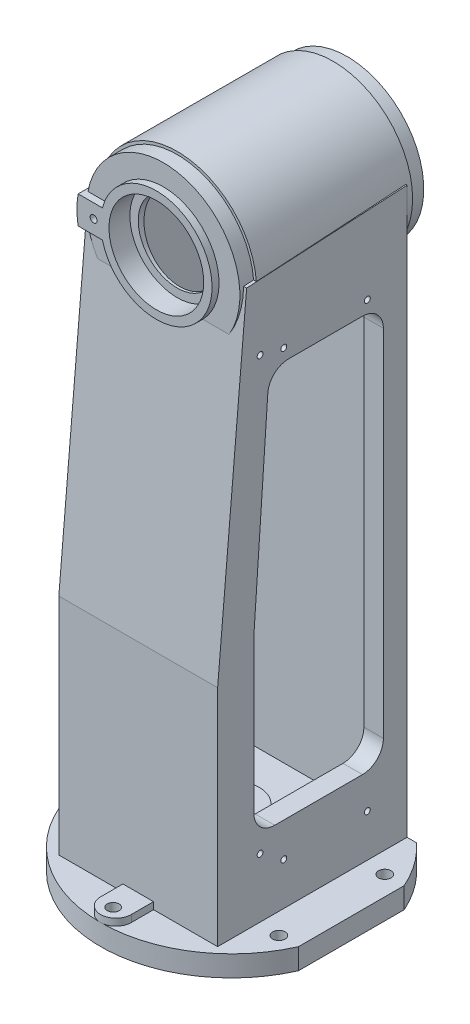
SolidWorks part; units mm, degrees
ref_plane "前视基准面" through (0, 0, 0) normal (0, 0, 1) x (1, 0, 0)
ref_plane "上视基准面" through (0, 0, 0) normal (0, 1, 0) x (1, 0, 0)
ref_plane "右视基准面" through (0, 0, 0) normal (1, 0, 0) x (0, 0, -1)
sketch "草图1" plane through (0, 0, 0) normal (0, 1, 0) x (1, 0, 0)
  line L0 (-86, 37.9473) -> (-86, -37.9473)
  line L1 (0, 0) -> (0, -70) construction
  line L2 (86, 37.9473) -> (86, -37.9473)
  line L5 (0, 0) -> (-62.7375, 0) construction
  line L6 (-63.8357, 69) -> (63.8357, 69)
  arc A0 (63.8357, 69) -> (86, 37.9473) centre (0, 0) cw
  arc A4 (-86, 37.9473) -> (-63.8357, 69) centre (0, 0) cw
  arc A5 (86, -37.9473) -> (-86, -37.9473) centre (0, 0) cw
  dimension "D2" = 69
  dimension "D3" = 94
  dimension "D1" = 172
extrude "凸台-拉伸1" add sketch "草图1" along normal blind 15
sketch "草图2" plane through (0, 15, 0) normal (0, 1, 0) x (1, 0, 0)
  line L0 (0, 0) -> (0, 57.4262) construction
  line L1 (0, 0) -> (-113.6406, 0) construction
  circle A0 centre (-72, 38) radius 4.5
  circle A1 centre (-72, -38) radius 4.5
  circle A2 centre (72, -38) radius 4.5
  circle A3 centre (72, 38) radius 4.5
  dimension "D3" = 9
  dimension "D1" = 144
  dimension "D2" = 76
extrude "切除-拉伸1" cut sketch "草图2" against normal through all
sketch "草图3" plane through (0, 15, 0) normal (0, 1, 0) x (1, 0, 0)
  line L0 (-11, -65) -> (-11, -83)
  line L1 (11, -83) -> (11, -65)
  line L2 (11, -65) -> (-11, -65)
  line L3 (0, 0) -> (0, -70.1629) construction
  arc A0 (-11, -83) -> (11, -83) centre (0, -83) ccw
  dimension "D1" = 83
  dimension "D2" = 11
  dimension "D3" = 18
extrude "凸台-拉伸2" add sketch "草图3" along normal blind 5
hole_wizard "孔1" positions "草图5" profile "草图4" legacy
sketch "草图5" plane through (0, 0, 0) normal (0, -1, 0) x (1, 0, 0)
  point P1 (0, 85)
  dimension "D1" = 85
sketch "草图4" plane through (0, 0, 85) normal (1, 0, 0) x (0, 0, -1)
  line L0 (0, 0) -> (0, 60)
  line L1 (0, 60) -> (4.25, 60)
  line L2 (4.25, 60) -> (4.25, 10)
  line L3 (4.25, 10) -> (7, 10)
  line L4 (7, 10) -> (7, 0)
  line L5 (7, 0) -> (0, 0)
  line L6 (0, 110) -> (0, -10) construction
  dimension "直径" = 8.5
  dimension "深度" = 60
  dimension "柱坑直径" = 14
  dimension "柱坑深度" = 10
sketch "草图7" plane through (0, 0, 0) normal (1, 0, 0) x (0, 0, -1)
  line L0 (-67, 15) -> (-67, 176)
  line L1 (-37.9473, 15) -> (-94, 15) construction
  line L2 (-94, 20) -> (-94, 15) construction
  line L3 (-67, 15) -> (69, 15)
  line L4 (-37.9473, 15) -> (37.9473, 15) construction
  line L5 (69, 15) -> (69, 420.4446)
  line L6 (69, 15) -> (69, 0) construction
  line L10 (-67, 176) -> (-46.172, 414.0647)
  line L12 (-46.172, 414.0647) -> (69, 420.4446)
  line L14 (-83, 20) -> (-65, 20) construction
  dimension "D1" = 27
  dimension "D2" = 156
  dimension "D3" = 175
extrude "凸台-拉伸3" add sketch "草图7" along normal mid plane 114
ref_plane "基准面1" through (0, 0, 54) normal (0, 0, 1) x (1, 0, 0)
sketch "草图8" plane through (0, 0, 54) normal (0, 0, 1) x (1, 0, 0)
  line L0 (-86, 0) -> (86, 0) construction
  circle A0 centre (0, 410) radius 40
  dimension "D1" = 80
  dimension "D2" = 410
extrude "凸台-拉伸4" add sketch "草图8" against normal blind 5 separate body
sketch "草图9" plane through (0, 0, 49) normal (0, 0, -1) x (-1, 0, 0)
  circle A0 centre (0, 410) radius 55
  dimension "D1" = 110
extrude "凸台-拉伸5" add sketch "草图9" along normal blind 10
sketch "草图10" plane through (0, 0, 39) normal (0, 0, -1) x (-1, 0, 0)
  circle A0 centre (0, 410) radius 57
  dimension "D1" = 114
extrude "凸台-拉伸6" add sketch "草图10" along normal blind 112
sketch "草图11" plane through (0, 0, -73) normal (0, 0, -1) x (-1, 0, 0)
  circle A0 centre (0, 410) radius 55
  dimension "D1" = 110
extrude "凸台-拉伸7" add sketch "草图11" along normal blind 10
sketch "草图12" plane through (0, 0, -83) normal (0, 0, -1) x (-1, 0, 0)
  circle A0 centre (0, 410) radius 40
  dimension "D1" = 80
extrude "凸台-拉伸8" add sketch "草图12" along normal blind 10
sketch "草图13" plane through (0, 0, 54) normal (0, 0, 1) x (1, 0, 0)
  circle A0 centre (0, 410) radius 34
  dimension "D1" = 68
extrude "切除-拉伸2" cut sketch "草图13" against normal blind 15
sketch "草图14" plane through (0, 0, -93) normal (0, 0, -1) x (-1, 0, 0)
  circle A0 centre (0, 410) radius 34
  dimension "D1" = 68
extrude "切除-拉伸3" cut sketch "草图14" against normal blind 15
sketch "草图15" plane through (0, 0, -78) normal (0, 0, -1) x (-1, 0, 0)
  circle A0 centre (0, 410) radius 28
  dimension "D1" = 56
extrude "切除-拉伸4" cut sketch "草图15" against normal through all
ref_plane "基准面2" through (0, 0, 34) normal (0, 0, 1) x (1, 0, 0)
sketch "草图16" plane through (0, 0, 34) normal (0, 0, 1) x (1, 0, 0)
  circle A0 centre (0, 410) radius 43
  dimension "D1" = 86
extrude "切除-拉伸5" cut sketch "草图16" against normal blind 105
sketch "草图17" plane through (0, 0, 0) normal (1, 0, 0) x (0, 0, -1)
  line L0 (-55, 29) -> (-55, 179)
  line L1 (-55, 179) -> (-34, 419.0311)
  line L2 (-34, 367) -> (-34, 453) construction
  line L3 (-34, 419.0311) -> (57, 419.0311)
  line L4 (57, 419.0311) -> (57, 29)
  line L5 (57, 29) -> (-55, 29)
  line L6 (-67, 176) -> (-67, 15) construction
  line L7 (69, 15) -> (69, 410) construction
  line L8 (37.9473, 0) -> (69, 0) construction
  line L9 (-46.172, 414.0647) -> (-67, 176) construction
  dimension "D1" = 12
  dimension "D2" = 12
  dimension "D3" = 29
  dimension "D4" = 150
extrude "切除-拉伸6" cut sketch "草图17" against normal mid plane 86
sketch "草图18" plane through (57, 0, 0) normal (1, 0, 0) x (0, 0, -1)
  line L0 (-41, 70) -> (52, 70)
  line L1 (52, 70) -> (52, 355)
  line L2 (52, 355) -> (-30, 355)
  line L3 (-30, 355) -> (-41, 195)
  line L4 (-41, 195) -> (-41, 70)
  line L5 (37.9473, 0) -> (69, 0) construction
  line L6 (69, 15) -> (69, 410) construction
  dimension "D1" = 70
  dimension "D2" = 285
  dimension "D3" = 93
  dimension "D4" = 82
  dimension "D5" = 17
  dimension "D6" = 125
extrude "切除-拉伸7" cut sketch "草图18" against normal up to next
fillet "圆角1" radius 15 4 edges at (50, 70, 41) (50, 70, -52) (50, 355, 30) (50, 355, -52)
sketch "草图19" plane through (0, 29, 0) normal (0, 1, 0) x (1, 0, 0)
  circle A0 centre (0, 0) radius 20
  dimension "D1" = 40
extrude "凸台-拉伸10" add sketch "草图19" along normal blind 13
hole_wizard "M20x2.5 螺纹孔1" positions "草图21" profile "草图20" tap size "M20x2.5" standard "JIS"
sketch "草图21" plane through (0, 0, 0) normal (0, -1, 0) x (1, 0, 0)
  point P1 (0, 0)
sketch "草图20" plane through (0, 0, 0) normal (1, 0, 0) x (0, 0, -1)
  line L0 (0, 0) -> (0, 47.2575)
  line L1 (0, 47.2575) -> (8.75, 42)
  line L2 (8.75, 42) -> (8.75, 0)
  line L5 (8.75, 0) -> (0, 0)
  line L10 (0, 47.2575) -> (-8.75, 42) construction
  line L11 (0, -6.35) -> (0, 107.95) construction
  dimension "螺纹孔钻头直径" = 17.5
  dimension "螺纹孔钻头深度" = 42
  dimension "导头角度" = 118
cosmetic thread "孔螺蚊线1" parameters "D1"=40, "D2"=20
sketch "草图22" plane through (0, 0, 54) normal (0, 0, 1) x (1, 0, 0)
  line L0 (-56.116, 420) -> (-38.7298, 420)
  line L1 (0, 410) -> (-95.1301, 410) construction
  line L2 (-56.116, 400) -> (-38.7298, 400)
  arc A0 (56.8251, 414.462) -> (-56.8251, 414.462) centre (0, 410) ccw construction
  circle A1 centre (0, 410) radius 40 construction
  arc A2 (-38.7298, 420) -> (-38.7298, 400) centre (0, 410) ccw
  arc A3 (-56.116, 420) -> (-56.116, 400) centre (0, 410) ccw
  dimension "D1" = 20
extrude "凸台-拉伸11" add sketch "草图22" against normal up to surface (15 mm away) up to face at (0, 440.231, 39)
hole_wizard "M6x1.0 螺纹孔1" positions "草图24" profile "草图23" tap size "M6x1.0" standard "JIS"
sketch "草图24" plane through (0, 0, 54) normal (0, 0, 1) x (1, 0, 0)
  line L0 (0, 410) -> (-45, 410) construction
  point P1 (-45, 410)
  dimension "D1" = 45
sketch "草图23" plane through (-45, 410, 54) normal (1, 0, 0) x (0, -1, 0)
  line L0 (0, 0) -> (0, 16.5022)
  line L1 (0, 16.5022) -> (2.5, 15)
  line L2 (2.5, 15) -> (2.5, 0)
  line L5 (2.5, 0) -> (0, 0)
  line L10 (0, 16.5022) -> (-2.5, 15) construction
  line L11 (0, -6.35) -> (0, 107.95) construction
  dimension "螺纹孔钻头直径" = 5
  dimension "螺纹孔钻头深度" = 15
  dimension "导头角度" = 118
cosmetic thread "孔螺蚊线2" parameters "D1"=12, "D2"=6
sketch "草图25" plane through (-43, 0, 0) normal (1, 0, 0) x (0, 0, -1)
  line L0 (-31, 138) -> (-31, 93) construction
  line L1 (-8.5, 138) -> (-8.5, 93)
  line L2 (-53.5, 138) -> (-53.5, 93)
  arc A0 (-8.5, 138) -> (-53.5, 138) centre (-31, 138) ccw
  arc A1 (-53.5, 93) -> (-8.5, 93) centre (-31, 93) ccw
  point P2 (-31, 115.5)
  dimension "D3" = 22.5
  dimension "D1" = 93
  dimension "D2" = 45
  dimension "D4" = 31
extrude "切除-拉伸8" cut sketch "草图25" against normal blind 3
sketch "草图26" plane through (-46, 0, 0) normal (1, 0, 0) x (0, 0, -1)
  circle A0 centre (-31, 138) radius 15
  circle A1 centre (-31, 93) radius 15
  dimension "D1" = 30
extrude "切除-拉伸9" cut sketch "草图26" against normal through all
sketch "草图27" plane through (-57, 0, 0) normal (-1, 0, 0) x (0, 0, 1)
  line L0 (6, 138) -> (6, 68)
  line L1 (6, 68) -> (56, 68)
  line L2 (56, 68) -> (56, 138)
  arc A0 (56, 138) -> (6, 138) centre (31, 138) ccw
  circle A1 centre (31, 138) radius 15 construction
  circle A2 centre (31, 93) radius 15 construction
  dimension "D1" = 25
  dimension "D2" = 25
extrude "切除-拉伸10" cut sketch "草图27" against normal blind 2
sketch "草图28" plane through (0, 0, -69) normal (0, 0, -1) x (-1, 0, 0)
  line L0 (-63.8357, 0) -> (63.8357, 0) construction
  circle A0 centre (0, 20) radius 12
  dimension "D2" = 24
  dimension "D1" = 20
extrude "凸台-拉伸12" add sketch "草图28" along normal blind 14
hole_wizard "M12x1.75 螺纹孔2" positions "草图30" profile "草图31" tap size "M12x1.75" standard "JIS"
sketch "草图30" plane through (0, 0, -83) normal (0, 0, -1) x (-1, 0, 0)
  point P1 (0, 20)
sketch "草图31" plane through (0, 20, -83) normal (1, 0, 0) x (0, 1, 0)
  line L0 (0, 0) -> (0, 74.25)
  line L1 (0, 74.25) -> (5.1, 74.25)
  line L2 (5.1, 74.25) -> (5.1, 0)
  line L5 (5.1, 0) -> (0, 0)
  line L11 (0, -6.35) -> (0, 107.95) construction
  dimension "通孔螺纹孔钻头直径" = 10.2
  dimension "通孔螺纹孔钻头深度" = 74.25
cosmetic thread "孔螺蚊线3" parameters "D2"=12
hole_wizard "M5x0.8 螺纹孔1" positions "草图33" profile "草图32" tap size "M5x0.8" standard "JIS"
sketch "草图33" plane through (57, 0, 0) normal (1, 0, 0) x (0, 0, -1)
  line L0 (52, 212.5) -> (-136.621, 212.5) construction
  line L1 (52, 85) -> (52, 340) construction
  line L3 (-41, 195) -> (-41, 85) construction
  point P1 (-36.5, 367.5)
  point P3 (-36.5, 57.5)
  dimension "D1" = 310
  dimension "D2" = 4.5
cosmetic thread "孔螺蚊线4" parameters "D2"=5
cosmetic thread "孔螺蚊线5" parameters "D2"=5
sketch "草图32" plane through (57, 367.5, 36.5) normal (0, 1, 0) x (0, 0, -1)
  line L0 (0, 0) -> (0, 14)
  line L1 (0, 14) -> (2.1, 14)
  line L2 (2.1, 14) -> (2.1, 0)
  line L5 (2.1, 0) -> (0, 0)
  line L11 (0, -6.35) -> (0, 107.95) construction
  dimension "通孔螺纹孔钻头直径" = 4.2
  dimension "通孔螺纹孔钻头深度" = 14
hole_wizard "M5x0.8 螺纹孔2" positions "草图35" profile "草图34" tap size "M5x0.8" standard "JIS"
sketch "草图35" plane through (57, 0, 0) normal (1, 0, 0) x (0, 0, -1)
  line L0 (52, 85) -> (52, 340) construction
  line L1 (37, 355) -> (-15.9958, 355) construction
  point P0 (40.5, 363.5)
  point P1 (-19.5, 363.5)
  point P7 (-19.5, 45.5)
  point P9 (40.5, 45.5)
  dimension "D1" = 60
  dimension "D2" = 11.5
  dimension "D3" = 8.5
  dimension "D4" = 318
cosmetic thread "孔螺蚊线6" parameters "D2"=5
cosmetic thread "孔螺蚊线7" parameters "D2"=5
cosmetic thread "孔螺蚊线8" parameters "D2"=5
cosmetic thread "孔螺蚊线9" parameters "D2"=5
sketch "草图34" plane through (57, 363.5, -40.5) normal (0, 1, 0) x (0, 0, -1)
  line L0 (0, 0) -> (0, 14)
  line L1 (0, 14) -> (2.1, 14)
  line L2 (2.1, 14) -> (2.1, 0)
  line L5 (2.1, 0) -> (0, 0)
  line L11 (0, -6.35) -> (0, 107.95) construction
  dimension "通孔螺纹孔钻头直径" = 4.2
  dimension "通孔螺纹孔钻头深度" = 14
hole_wizard "M5x0.8 螺纹孔3" positions "草图37" profile "草图36" tap size "M5x0.8" standard "JIS"
sketch "草图37" plane through (-57, 0, 0) normal (-1, 0, 0) x (0, 0, 1)
  line L0 (-69, 15) -> (-69, 410) construction
  line L1 (-69, 0) -> (-37.9473, 0) construction
  line L2 (-69, 15) -> (-69, 410) construction
  point P1 (-24, 145)
  point P3 (-31.5, 315)
  point P5 (18.5, 315)
  point P11 (-57, 110)
  point P13 (-42, 110)
  dimension "D2" = 50
  dimension "D3" = 37.5
  dimension "D4" = 145
  dimension "D5" = 45
  dimension "D6" = 315
  dimension "D7" = 12
  dimension "D8" = 15
  dimension "D9" = 110
sketch "草图36" plane through (-57, 145, -24) normal (0, 1, 0) x (0, 0, 1)
  line L0 (0, 0) -> (0, 15.2618)
  line L1 (0, 15.2618) -> (2.1, 14)
  line L2 (2.1, 14) -> (2.1, 0)
  line L5 (2.1, 0) -> (0, 0)
  line L10 (0, 15.2618) -> (-2.1, 14) construction
  line L11 (0, -6.35) -> (0, 107.95) construction
  dimension "螺纹孔钻头直径" = 4.2
  dimension "螺纹孔钻头深度" = 14
  dimension "导头角度" = 118
cosmetic thread "孔螺蚊线10" parameters "D1"=10, "D2"=5
cosmetic thread "孔螺蚊线11" parameters "D1"=10, "D2"=5
cosmetic thread "孔螺蚊线12" parameters "D1"=10, "D2"=5
cosmetic thread "孔螺蚊线13" parameters "D1"=10, "D2"=5
cosmetic thread "孔螺蚊线18" parameters "D1"=10, "D2"=5
hole_wizard "M5x0.8 螺纹孔4" positions "草图39" profile "草图38" tap size "M5x0.8" standard "JIS"
sketch "草图39" plane through (-57, 0, 0) normal (-1, 0, 0) x (0, 0, 1)
  line L0 (-69, 15) -> (-69, 410) construction
  point P0 (36, 240)
  point P1 (-54, 240)
  point P3 (-54, 400)
  point P5 (36, 400)
  dimension "D1" = 160
  dimension "D2" = 90
  dimension "D3" = 15
  dimension "D4" = 240
sketch "草图38" plane through (-57, 240, 36) normal (0, 1, 0) x (0, 0, 1)
  line L0 (0, 0) -> (0, 15.2618)
  line L1 (0, 15.2618) -> (2.1, 14)
  line L2 (2.1, 14) -> (2.1, 0)
  line L5 (2.1, 0) -> (0, 0)
  line L10 (0, 15.2618) -> (-2.1, 14) construction
  line L11 (0, -6.35) -> (0, 107.95) construction
  dimension "螺纹孔钻头直径" = 4.2
  dimension "螺纹孔钻头深度" = 14
  dimension "导头角度" = 118
cosmetic thread "孔螺蚊线14" parameters "D1"=10, "D2"=5
cosmetic thread "孔螺蚊线15" parameters "D1"=10, "D2"=5
cosmetic thread "孔螺蚊线16" parameters "D1"=10, "D2"=5
cosmetic thread "孔螺蚊线17" parameters "D1"=10, "D2"=5
fillet "圆角2" radius 5 2 edges at (-56, 68, 56) (-56, 68, 6)
hole_wizard "M3x0.5 螺纹孔1" positions "草图41" profile "草图40" tap size "M3x0.5" standard "JIS"
sketch "草图41" plane through (-55, 0, 0) normal (-1, 0, 0) x (0, 0, 1)
  line L0 (31, 93) -> (31, 115.958) construction
  line L2 (31, 93) -> (-7.1004, 93) construction
  point P1 (16, 108)
  point P14 (16, 78)
  point P15 (46, 78)
  point P16 (46, 108)
  dimension "D1" = 30
  dimension "D2" = 30
sketch "草图40" plane through (-55, 108, 16) normal (0, 1, 0) x (0, 0, 1)
  line L0 (0, 0) -> (0, 8.2511)
  line L1 (0, 8.2511) -> (1.25, 7.5)
  line L2 (1.25, 7.5) -> (1.25, 0)
  line L5 (1.25, 0) -> (0, 0)
  line L10 (0, 8.2511) -> (-1.25, 7.5) construction
  line L11 (0, -6.35) -> (0, 107.95) construction
  dimension "螺纹孔钻头直径" = 2.5
  dimension "螺纹孔钻头深度" = 7.5
  dimension "导头角度" = 118
cosmetic thread "孔螺蚊线20" parameters "D1"=6, "D2"=3
cosmetic thread "孔螺蚊线21" parameters "D1"=6, "D2"=3
cosmetic thread "孔螺蚊线22" parameters "D1"=6, "D2"=3
cosmetic thread "孔螺蚊线23" parameters "D1"=6, "D2"=3
